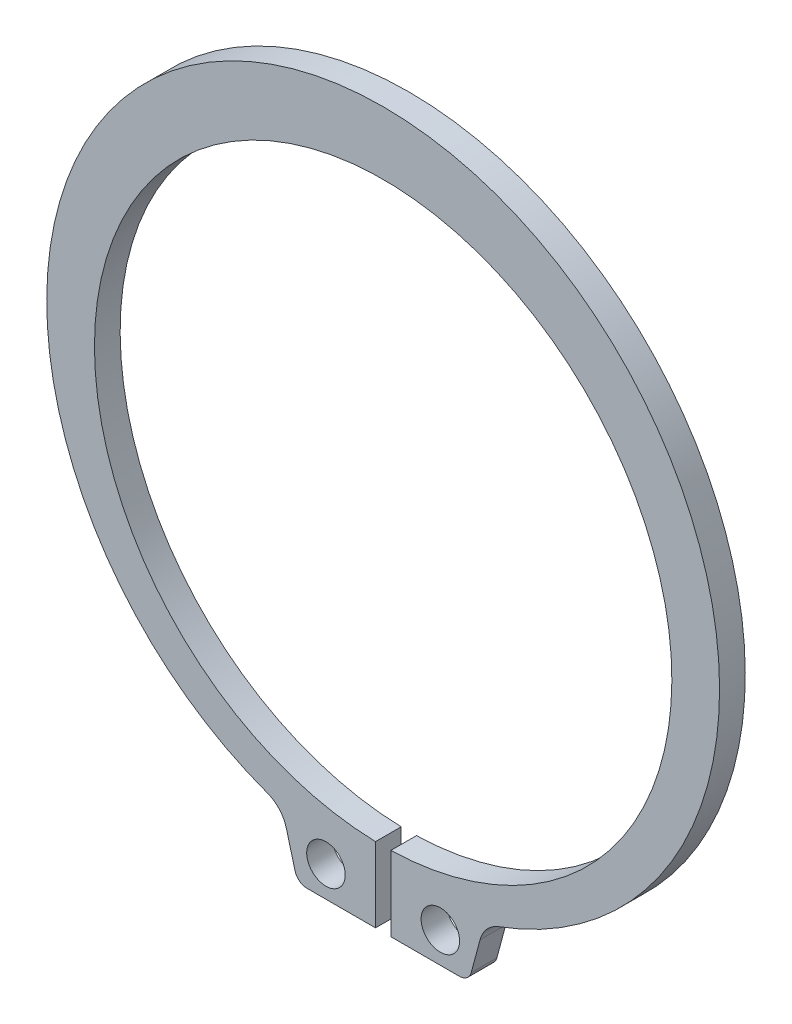
SolidWorks part; units mm, degrees
material "Alloy Steel"
ref_plane "Front Plane" through (0, 0, 0) normal (0, 0, 1) x (1, 0, 0)
ref_plane "Top Plane" through (0, 0, 0) normal (0, 1, 0) x (1, 0, 0)
ref_plane "Right Plane" through (0, 0, 0) normal (1, 0, 0) x (0, 0, -1)
sketch "Base Sketch" plane through (0, 0, 0) normal (0, 0, 1) x (1, 0, 0)
  line L0 (0, -13.97) -> (0, -15.7226)
  line L3 (-3.1662, -15.7226) -> (3.1662, -15.7226)
  line L4 (3.6569, -15.3461) -> (4.0233, -13.9784)
  line L5 (3.556, -15.7226) -> (3.556, -9.2558) construction
  line L6 (0, 11.3538) -> (0, -12.6238) construction
  line L7 (-3.6569, -15.3461) -> (-4.0233, -13.9784)
  line L8 (0, -13.97) -> (0, -15.7226) construction
  arc A0 (4.8126, -13.1149) -> (-4.8126, -13.1149) centre (0, 0) ccw
  circle A1 centre (0, -0.635) radius 11.9888
  arc A2 (3.1662, -15.7226) -> (3.6569, -15.3461) centre (3.1662, -15.2146) ccw
  arc A3 (4.0233, -13.9784) -> (4.8126, -13.1149) centre (5.2501, -14.3071) cw
  circle A4 centre (2.3749, -14.4526) radius 0.8001
  circle A5 centre (-2.3749, -14.4526) radius 0.8001
  arc A6 (-3.1662, -15.7226) -> (-3.6569, -15.3461) centre (-3.1662, -15.2146) cw
  arc A7 (-4.0233, -13.9784) -> (-4.8126, -13.1149) centre (-5.2501, -14.3071) ccw
  point P18 (-2.3749, -14.4526)
  dimension "D1" = 27.94
  dimension "D2" = 23.9776
  dimension "D4" = 15
  dimension "D7" = 0.508
  dimension "D8" = 1.27
  dimension "D9" = 1.6002
  dimension "D3" = 0.635
  dimension "D5" = 159.714
  dimension "D6" = 3.556
  dimension "D10" = 2.3749
  dimension "D11" = 1.27
  dimension "D12" = 6.4668
  dimension "D13" = 2.4234
extrude "Base" add sketch "Base Sketch" along normal blind 1.0668
sketch "Cut Sketch" plane through (0, 0, 1.0668) normal (0, 0, 1) x (1, 0, 0)
  line L1 (0.3175, -16.353) -> (-0.3175, -16.353)
  line L2 (0.3175, -16.353) -> (0.3175, -8.8946)
  line L3 (0.3175, -8.8946) -> (-0.3175, -8.8946)
  line L4 (-0.3175, -16.353) -> (-0.3175, -8.8946)
  line L5 (0.3175, -16.353) -> (-0.3175, -8.8946) construction
  line L6 (0.3175, -8.8946) -> (-0.3175, -16.353) construction
  circle A0 centre (0, -0.635) radius 11.9888 construction
  circle A1 centre (-2.3749, -14.4526) radius 0.8001 construction
  point P0 (0, -12.6238)
  dimension "D1" = 0.635
  dimension "D2" = 7.4583
  dimension "D3" = 2.9974
extrude "Bottom Cut" cut sketch "Cut Sketch" against normal through all
